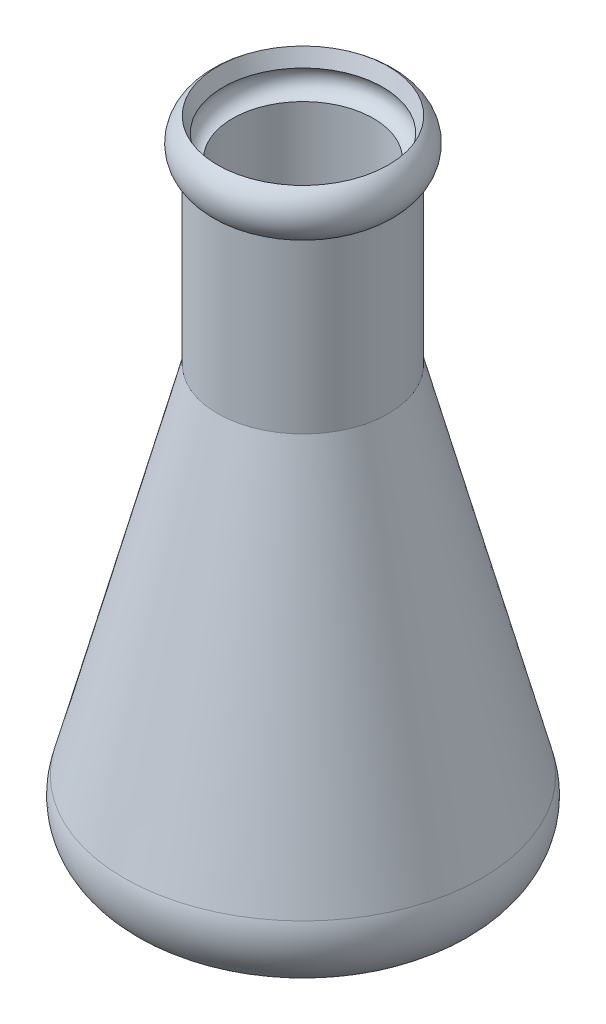
SolidWorks part; units mm, degrees
ref_plane "Płaszczyzna przednia" through (0, 0, 0) normal (0, 0, 1) x (1, 0, 0)
ref_plane "Płaszczyzna górna" through (0, 0, 0) normal (0, 1, 0) x (1, 0, 0)
ref_plane "Płaszczyzna prawa" through (0, 0, 0) normal (1, 0, 0) x (0, 0, -1)
sketch "Sketch1" plane through (0, 0, 0) normal (0, 0, 1) x (1, 0, 0)
  line L0 (874.5891, 407.8122) -> (874.5891, 492.8122) construction
  line L4 (11.3689, -6.3151) -> (11.3689, -28.6552)
  line L5 (11.3689, -28.6552) -> (23.7891, -76.0053)
  line L6 (0, -85) -> (20.3122, -85)
  line L8 (2, -83) -> (19.725, -83)
  line L9 (9.3689, -28.9131) -> (21.8671, -76.5606)
  line L10 (9.3689, -4.9882) -> (9.3689, -28.9131)
  line L12 (10.6139, -2) -> (11.3689, 0)
  line L13 (2, -83) -> (0, -83)
  line L14 (0, -85) -> (0, -83)
  line L15 (2, -2) -> (2, -83) construction
  line L16 (0, 0) -> (0, -85) construction
  line L19 (2, -2) -> (10.6139, -2) construction
  line L20 (0, 0) -> (11.3689, 0) construction
  arc A0 (20.3122, -85) -> (23.7891, -76.0053) centre (16.391, -78.3149) ccw
  arc A1 (11.3689, -6.3151) -> (11.3689, 0) centre (9.1836, -3.1576) ccw
  arc A2 (19.725, -83) -> (21.8671, -76.5606) centre (16.391, -78.3149) ccw
  arc A3 (9.3689, -4.9882) -> (10.6139, -2) centre (9.1836, -3.1576) ccw
  dimension "D1" = 85
  dimension "D3" = 2
revolve "Revolve1" add sketch "Sketch1" angle 360 about L14
